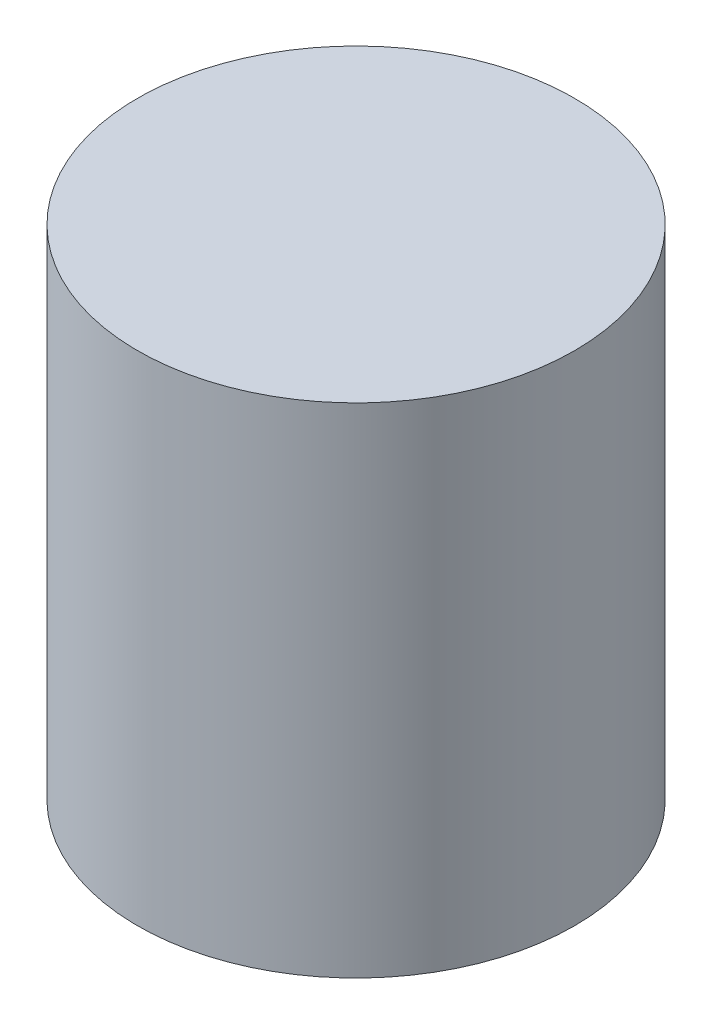
SolidWorks part; units mm, degrees
material "PVC Rigid"
ref_plane "Front Plane" through (0, 0, 0) normal (0, 0, 1) x (1, 0, 0)
ref_plane "Top Plane" through (0, 0, 0) normal (0, 1, 0) x (1, 0, 0)
ref_plane "Right Plane" through (0, 0, 0) normal (1, 0, 0) x (0, 0, -1)
sketch "Sketch1" plane through (0, 0, 0) normal (0, 0, 1) x (1, 0, 0)
  line L0 (0, -941.7013) -> (0, 46143.3621) construction
  line L1 (-22.6, -14.9757) -> (-22.6, 39.7243)
  line L2 (-22.6, 39.7243) -> (0, 39.7243)
  line L3 (-22.6, -14.9757) -> (-25.1, -14.9757)
  line L4 (-25.1, -14.9757) -> (-25.1, 42.2243)
  line L5 (-25.1, 42.2243) -> (0, 42.2243)
  line L6 (0, 42.2243) -> (0, 39.7243)
  dimension "D1" = 22.6
  dimension "D2" = 54.7
  dimension "D3" = 2.5
  dimension "D4" = 2.5
revolve "Revolve1" add sketch "Sketch1" angle 360 about L0
